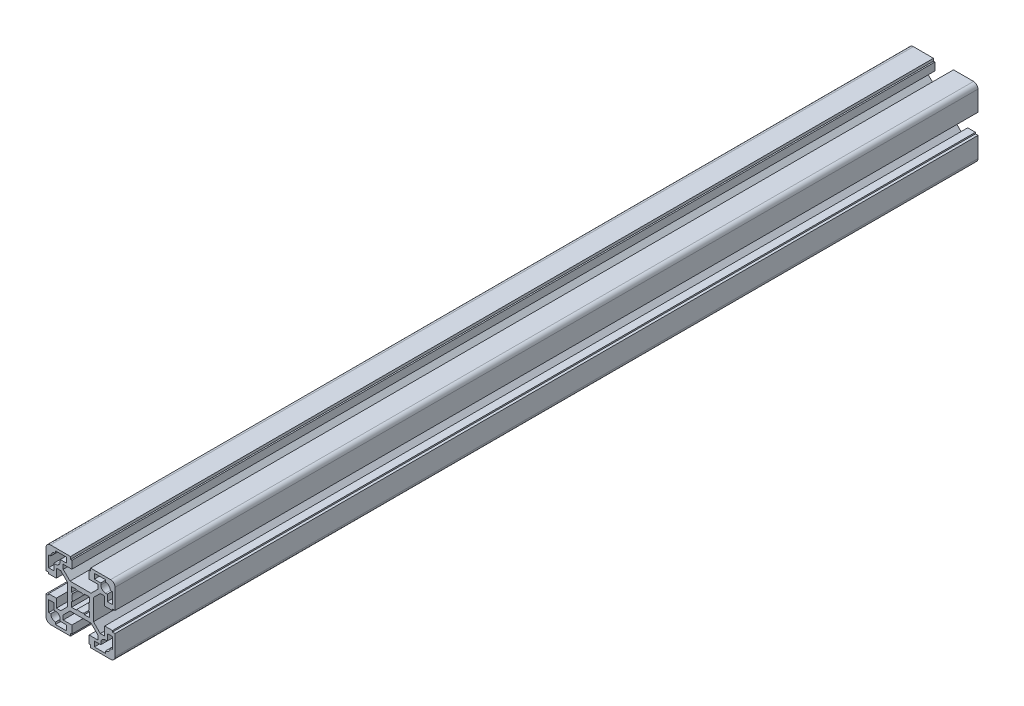
SolidWorks part; units mm, degrees
ref_plane "Piano frontale" through (0, 0, 0) normal (0, 0, 1) x (1, 0, 0)
ref_plane "Piano superiore" through (0, 0, 0) normal (0, 1, 0) x (1, 0, 0)
ref_plane "Piano destro" through (0, 0, 0) normal (1, 0, 0) x (0, 0, -1)
sketch "Schizzo1" plane through (0, 0, 0) normal (0, 0, 1) x (1, 0, 0)
  line L0 (0, -20) -> (0, 20) construction
  line L1 (-20, 0) -> (20, 0) construction
  line L2 (-5.2, 5.2) -> (-2.26, 5.2)
  line L3 (-11.75, 15.5) -> (-11.75, 14.5)
  line L4 (-18.5, 14.5) -> (-17.25, 14.5)
  line L5 (-1.993, 4.5856) -> (-2.26, 5.2)
  line L6 (-5, 18.5) -> (-5, 14)
  line L7 (0, 0) -> (-20, 20) construction
  line L8 (6.085, 7.5) -> (-6.085, 7.5)
  line L9 (-6.085, 7.5) -> (-10.0587, 11.46)
  line L10 (-10.0587, 11.46) -> (-10.0587, 14)
  line L11 (-10.0587, 14) -> (-5, 14)
  line L12 (-5, 18.5) -> (-5.8, 18.5)
  line L13 (-5.8, 18.5) -> (-5.8, 20)
  line L14 (-5.8, 20) -> (-17.4314, 20)
  line L15 (-14.5, 18.5) -> (-8, 18.5)
  line L16 (-8, 18.5) -> (-8, 15.5)
  line L17 (-8, 15.5) -> (-11.75, 15.5)
  line L18 (-14.5, 18.5) -> (-14.5, 17.25)
  line L19 (-15.5, 8) -> (-15.5, 11.75)
  line L20 (-18.5, 8) -> (-15.5, 8)
  line L21 (-18.5, 14.5) -> (-18.5, 8)
  line L22 (-20, 5.8) -> (-20, 17.4314)
  line L23 (-18.5, 5.8) -> (-20, 5.8)
  line L24 (-18.5, 5) -> (-18.5, 5.8)
  line L25 (-14, 10.0587) -> (-14, 5)
  line L26 (-11.46, 10.0587) -> (-14, 10.0587)
  line L27 (-7.5, 6.085) -> (-11.46, 10.0587)
  line L28 (-7.5, -6.085) -> (-7.5, 6.085)
  line L29 (-18.5, 5) -> (-14, 5)
  line L30 (-4.5856, 1.993) -> (-5.2, 2.26)
  line L31 (-15.5, 11.75) -> (-14.5, 11.75)
  line L32 (-5.2, 5.2) -> (-5.2, 2.26)
  line L33 (0, 0) -> (20, 20) construction
  line L34 (5.2, 5.2) -> (5.2, 2.26)
  line L35 (15.5, 11.75) -> (14.5, 11.75)
  line L36 (4.5856, 1.993) -> (5.2, 2.26)
  line L37 (18.5, 5) -> (14, 5)
  line L38 (7.5, -6.085) -> (7.5, 6.085)
  line L39 (7.5, 6.085) -> (11.46, 10.0587)
  line L40 (11.46, 10.0587) -> (14, 10.0587)
  line L41 (14, 10.0587) -> (14, 5)
  line L42 (18.5, 5) -> (18.5, 5.8)
  line L43 (18.5, 5.8) -> (20, 5.8)
  line L44 (20, 5.8) -> (20, 17.4314)
  line L45 (18.5, 14.5) -> (18.5, 8)
  line L46 (18.5, 8) -> (15.5, 8)
  line L47 (15.5, 8) -> (15.5, 11.75)
  line L48 (14.5, 18.5) -> (14.5, 17.25)
  line L49 (8, 15.5) -> (11.75, 15.5)
  line L50 (8, 18.5) -> (8, 15.5)
  line L51 (14.5, 18.5) -> (8, 18.5)
  line L52 (5.8, 20) -> (17.4314, 20)
  line L53 (5.8, 18.5) -> (5.8, 20)
  line L54 (5, 18.5) -> (5.8, 18.5)
  line L55 (10.0587, 14) -> (5, 14)
  line L56 (10.0587, 11.46) -> (10.0587, 14)
  line L57 (6.085, 7.5) -> (10.0587, 11.46)
  line L58 (5, 18.5) -> (5, 14)
  line L59 (1.993, 4.5856) -> (2.26, 5.2)
  line L60 (18.5, 14.5) -> (17.25, 14.5)
  line L61 (11.75, 15.5) -> (11.75, 14.5)
  line L62 (5.2, 5.2) -> (2.26, 5.2)
  line L63 (0, 0) -> (20, -20) construction
  line L64 (0, 0) -> (-20, -20) construction
  line L65 (5.2, -5.2) -> (2.26, -5.2)
  line L66 (11.75, -15.5) -> (11.75, -14.5)
  line L67 (18.5, -14.5) -> (17.25, -14.5)
  line L68 (1.993, -4.5856) -> (2.26, -5.2)
  line L69 (5, -18.5) -> (5, -14)
  line L70 (6.085, -7.5) -> (10.0587, -11.46)
  line L71 (10.0587, -11.46) -> (10.0587, -14)
  line L72 (10.0587, -14) -> (5, -14)
  line L73 (5, -18.5) -> (5.8, -18.5)
  line L74 (5.8, -18.5) -> (5.8, -20)
  line L75 (5.8, -20) -> (17.4314, -20)
  line L76 (14.5, -18.5) -> (8, -18.5)
  line L77 (8, -18.5) -> (8, -15.5)
  line L78 (8, -15.5) -> (11.75, -15.5)
  line L79 (14.5, -18.5) -> (14.5, -17.25)
  line L80 (15.5, -8) -> (15.5, -11.75)
  line L81 (18.5, -8) -> (15.5, -8)
  line L82 (18.5, -14.5) -> (18.5, -8)
  line L83 (20, -5.8) -> (20, -17.4314)
  line L84 (18.5, -5.8) -> (20, -5.8)
  line L85 (18.5, -5) -> (18.5, -5.8)
  line L86 (14, -10.0587) -> (14, -5)
  line L87 (11.46, -10.0587) -> (14, -10.0587)
  line L88 (7.5, -6.085) -> (11.46, -10.0587)
  line L89 (18.5, -5) -> (14, -5)
  line L90 (4.5856, -1.993) -> (5.2, -2.26)
  line L91 (15.5, -11.75) -> (14.5, -11.75)
  line L92 (5.2, -5.2) -> (5.2, -2.26)
  line L93 (-5.2, -5.2) -> (-5.2, -2.26)
  line L94 (-15.5, -11.75) -> (-14.5, -11.75)
  line L95 (-4.5856, -1.993) -> (-5.2, -2.26)
  line L96 (-18.5, -5) -> (-14, -5)
  line L97 (-7.5, -6.085) -> (-11.46, -10.0587)
  line L98 (-11.46, -10.0587) -> (-14, -10.0587)
  line L99 (-14, -10.0587) -> (-14, -5)
  line L100 (-18.5, -5) -> (-18.5, -5.8)
  line L101 (-18.5, -5.8) -> (-20, -5.8)
  line L102 (-20, -5.8) -> (-20, -17.4314)
  line L103 (-18.5, -14.5) -> (-18.5, -8)
  line L104 (-18.5, -8) -> (-15.5, -8)
  line L105 (-15.5, -8) -> (-15.5, -11.75)
  line L106 (-14.5, -18.5) -> (-14.5, -17.25)
  line L107 (-8, -15.5) -> (-11.75, -15.5)
  line L108 (-8, -18.5) -> (-8, -15.5)
  line L109 (-14.5, -18.5) -> (-8, -18.5)
  line L110 (-5.8, -20) -> (-17.4314, -20)
  line L111 (-5.8, -18.5) -> (-5.8, -20)
  line L112 (-5, -18.5) -> (-5.8, -18.5)
  line L113 (-10.0587, -14) -> (-5, -14)
  line L114 (-10.0587, -11.46) -> (-10.0587, -14)
  line L115 (-6.085, -7.5) -> (-10.0587, -11.46)
  line L116 (6.085, -7.5) -> (-6.085, -7.5)
  line L117 (-5, -18.5) -> (-5, -14)
  line L118 (-1.993, -4.5856) -> (-2.26, -5.2)
  line L119 (-18.5, -14.5) -> (-17.25, -14.5)
  line L120 (-11.75, -15.5) -> (-11.75, -14.5)
  line L121 (-5.2, -5.2) -> (-2.26, -5.2)
  arc A0 (1.993, 4.5856) -> (-1.993, 4.5856) centre (0, 0) ccw
  arc A1 (-14.5, 17.25) -> (-17.25, 14.5) centre (-14.5, 14.5) ccw
  arc A2 (-4.5856, -1.993) -> (-4.5856, 1.993) centre (0, 0) cw
  arc A3 (-14.5, 11.75) -> (-11.75, 14.5) centre (-14.5, 14.5) ccw
  arc A4 (-17.4314, 20) -> (-20, 17.4314) centre (-17.4314, 17.4314) ccw
  arc A5 (17.4314, 20) -> (20, 17.4314) centre (17.4314, 17.4314) cw
  arc A6 (14.5, 11.75) -> (11.75, 14.5) centre (14.5, 14.5) cw
  arc A7 (4.5856, -1.993) -> (4.5856, 1.993) centre (0, 0) ccw
  arc A8 (14.5, 17.25) -> (17.25, 14.5) centre (14.5, 14.5) cw
  arc A9 (14.5, -17.25) -> (17.25, -14.5) centre (14.5, -14.5) ccw
  arc A10 (14.5, -11.75) -> (11.75, -14.5) centre (14.5, -14.5) ccw
  arc A11 (17.4314, -20) -> (20, -17.4314) centre (17.4314, -17.4314) ccw
  arc A12 (-17.4314, -20) -> (-20, -17.4314) centre (-17.4314, -17.4314) cw
  arc A13 (-14.5, -11.75) -> (-11.75, -14.5) centre (-14.5, -14.5) cw
  arc A14 (-14.5, -17.25) -> (-17.25, -14.5) centre (-14.5, -14.5) cw
  arc A15 (1.993, -4.5856) -> (-1.993, -4.5856) centre (0, 0) cw
  point P4 (0, 0)
  point P8 (0, 0)
  point P14 (-2.26, 5.2)
  point P15 (0, 0)
  point P19 (-20, 20)
  point P47 (-5.2, 2.26)
  point P50 (-11.75, 11.75)
  point P51 (0, 0)
  point P52 (0, 0)
  point P53 (0, 0)
  point P92 (0, 7.5)
  point P93 (11.75, 11.75)
  point P94 (5.2, 2.26)
  point P95 (20, 20)
  point P96 (2.26, 5.2)
  point P141 (7.5, 0)
  point P148 (-7.5, 0)
  point P167 (2.26, -5.2)
  point P168 (20, -20)
  point P169 (5.2, -2.26)
  point P170 (11.75, -11.75)
  point P171 (0, -7.5)
  point P172 (-11.75, -11.75)
  point P173 (-5.2, -2.26)
  point P174 (-20, -20)
  point P175 (-2.26, -5.2)
  dimension "D5" = 5
  dimension "D3" = 2.75
  dimension "D6" = 2.5686
  dimension "D1" = 40
  dimension "D2" = 40
  dimension "D4" = 5.2
  dimension "D7" = 2.94
  dimension "D9" = 0.6144
  dimension "D10" = 20
  dimension "D11" = 20
  dimension "D12" = 5
  dimension "D13" = 13.3
  dimension "D14" = 4.5
  dimension "D15" = 6.085
  dimension "D16" = 3.96
  dimension "D17" = 2.54
  dimension "D18" = 5.61
  dimension "D19" = 0.8
  dimension "D20" = 6.5
  dimension "D21" = 3
  dimension "D22" = 1.25
  dimension "D23" = 2.75
  dimension "D24" = 3
extrude "Estrusione-Estrusione1" add sketch "Schizzo1" along normal blind 500
ref_plane "Piano1" through (20, 0, 0) normal (1, 0, 0) x (0, 0, -1)
sketch "Schizzo3" plane through (20, 0, 0) normal (1, 0, 0) x (0, 0, -1)
  line L1 (-40, -20) -> (0, -20) construction
  line L2 (-40, -20) -> (-40, 20) construction
  line L3 (-40, 20) -> (0, 20) construction
  line L4 (0, -20) -> (0, 20) construction
  line L5 (-40, -20) -> (0, 20) construction
  line L6 (-40, 20) -> (0, -20) construction
  line L7 (-460, -20) -> (-500, -20)
  line L8 (-460, -20) -> (-460, 20)
  line L9 (-460, 20) -> (-500, 20)
  line L10 (-500, -20) -> (-500, 20)
  line L11 (-460, -20) -> (-500, 20) construction
  line L12 (-460, 20) -> (-500, -20) construction
  point P0 (-20, 0)
  point P6 (-480, 0)
  dimension "D1" = 40
  dimension "D2" = 40
  dimension "D3" = 40
  dimension "D4" = 40
